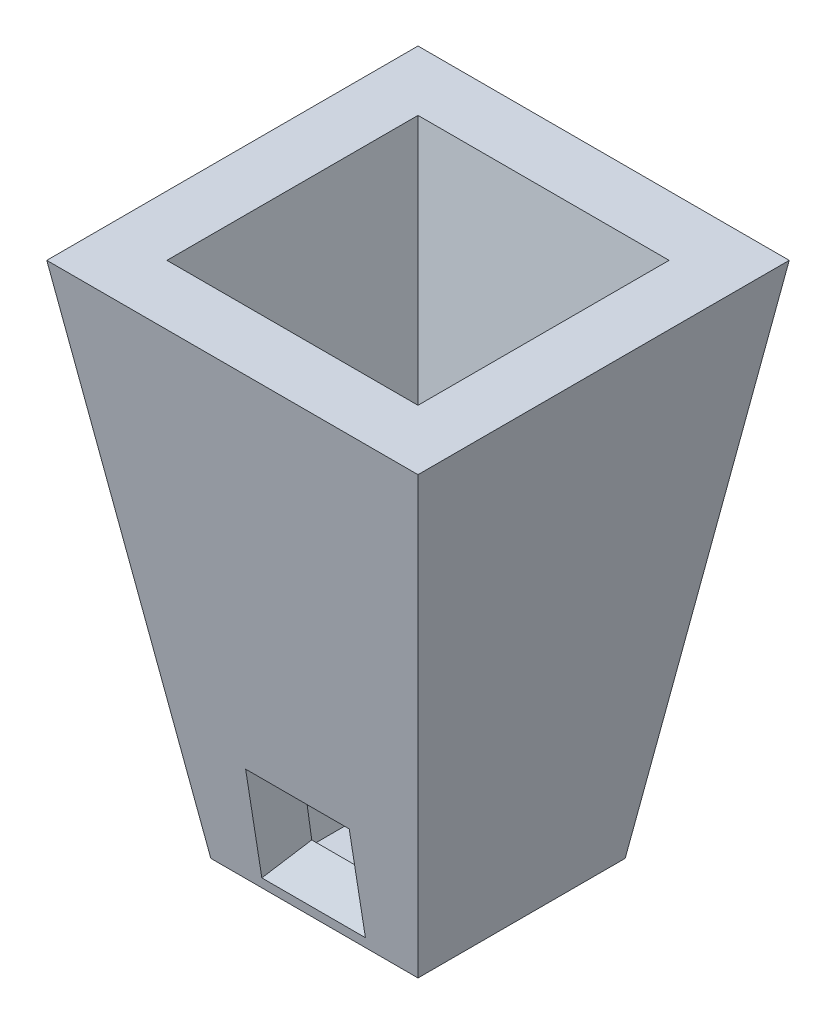
SolidWorks part; units mm, degrees
ref_plane "Front Plane" through (0, 0, 0) normal (0, 0, 1) x (1, 0, 0)
ref_plane "Top Plane" through (0, 0, 0) normal (0, 1, 0) x (1, 0, 0)
ref_plane "Right Plane" through (0, 0, 0) normal (1, 0, 0) x (0, 0, -1)
sketch "Sketch1" plane through (0, 0, 0) normal (0, 1, 0) x (1, 0, 0)
  line L1 (-43.5142, 7.624) -> (7.2858, 7.624)
  line L2 (-43.5142, 7.624) -> (-43.5142, -43.176)
  line L3 (-43.5142, -43.176) -> (7.2858, -43.176)
  line L4 (7.2858, 7.624) -> (7.2858, -43.176)
  dimension "D1" = 50.8
  dimension "D2" = 50.8
extrude "Boss-Extrude1" add sketch "Sketch1" along normal blind 127 draft 9 contours L2 L1 L4 L3 draft outward yes
sketch "Sketch2" plane through (0, 127, 0) normal (0, 1, 0) x (1, 0, 0)
  line L0 (-63.629, 27.7389) -> (-63.629, -63.2908) construction
  line L1 (-48.897, 13.0069) -> (12.6686, 13.0069)
  line L2 (-48.897, 13.0069) -> (-48.897, -48.5588)
  line L3 (-48.897, -48.5588) -> (12.6686, -48.5588)
  line L4 (12.6686, 13.0069) -> (12.6686, -48.5588)
  line L5 (27.4006, 27.7389) -> (27.4006, -63.2908) construction
  line L6 (-63.629, -63.2908) -> (27.4006, -63.2908) construction
  line L7 (-63.629, 27.7389) -> (27.4006, 27.7389) construction
  dimension "D1" = 14.732
  dimension "D2" = 14.732
  dimension "D3" = 14.732
  dimension "D4" = 14.732
extrude "Cut-Extrude1" cut sketch "Sketch2" against normal blind 124.46 draft 8 contours L2 L1 L4 L3
sketch "Sketch3" plane through (0, -6.6711, 42.1194) normal (0, -0.1564, 0.9877) x (1, 0, 0)
  line L0 (-43.5142, 6.7542) -> (7.2858, 6.7542) construction
  line L1 (-30.609, 34.6942) -> (-5.209, 34.6942)
  line L2 (-30.609, 34.6942) -> (-30.609, 9.2942)
  line L3 (-30.609, 9.2942) -> (-5.209, 9.2942)
  line L4 (-5.209, 34.6942) -> (-5.209, 9.2942)
  line L7 (-63.629, 135.3373) -> (-63.629, 6.7542) construction
  line L8 (-63.629, 6.7542) -> (-43.5142, 6.7542) construction
  line L9 (-43.5142, 6.7542) -> (-63.629, 135.3373) construction
  dimension "D1" = 2.54
  dimension "D2" = 25.4
  dimension "D3" = 25.4
  dimension "D4" = 33.02
extrude "Cut-Extrude2" cut sketch "Sketch3" against normal up to next
sketch "Sketch4" plane through (0, -1.178, -7.4375) normal (0, -0.1564, -0.9877) x (-1, 0, 0)
  line L0 (43.5142, 1.1927) -> (-7.2858, 1.1927) construction
  line L1 (5.6194, 29.1327) -> (31.0194, 29.1327)
  line L2 (5.6194, 29.1327) -> (5.6194, 3.7327)
  line L3 (5.6194, 3.7327) -> (31.0194, 3.7327)
  line L4 (31.0194, 29.1327) -> (31.0194, 3.7327)
  line L5 (-27.4006, 129.7757) -> (-27.4006, 1.1927) construction
  line L6 (63.629, 129.7757) -> (63.629, 1.1927) construction
  dimension "D1" = 25.4
  dimension "D2" = 25.4
  dimension "D3" = 2.54
  dimension "D4" = 33.02
extrude "Cut-Extrude3" cut sketch "Sketch4" against normal up to next contours L2 L1 L4 L3
